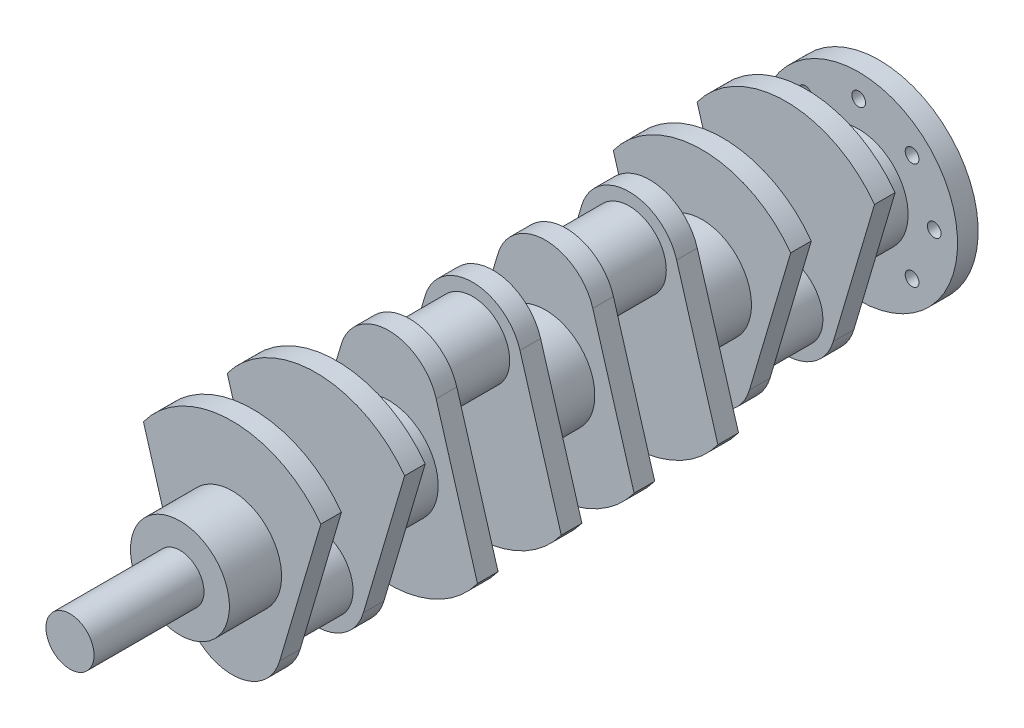
SolidWorks part; units mm, degrees
ref_plane "Front Plane" through (0, 0, 0) normal (0, 0, 1) x (1, 0, 0)
ref_plane "Top Plane" through (0, 0, 0) normal (0, 1, 0) x (1, 0, 0)
ref_plane "Right Plane" through (0, 0, 0) normal (1, 0, 0) x (0, 0, -1)
sketch "Sketch1" plane through (0, 0, 0) normal (0, 0, 1) x (1, 0, 0)
  line L0 (0, 0) -> (0, 85088.2175) construction
  line L1 (0, 0) -> (-85088.2175, 0) construction
  line L2 (-64.5699, 47.2306) -> (-34.5175, -54.2246)
  line L3 (64.5699, 47.2306) -> (34.5175, -54.2246)
  circle A0 centre (0, -44) radius 36
  arc A1 (-64.5699, 47.2306) -> (64.5699, 47.2306) centre (0, 0) cw
  dimension "D1" = 72
  dimension "D3" = 80
  dimension "D2" = 44
  dimension "D4" = 33
extrude "Boss-Extrude1" add sketch "Sketch1" along normal blind 15 contours A1 L2 A0 L3 | A0
sketch "Sketch2" plane through (0, 0, 15) normal (0, 0, 1) x (1, 0, 0)
  circle A0 centre (0, -44) radius 27
  dimension "D1" = 54
extrude "Boss-Extrude2" add sketch "Sketch2" along normal blind 46
sketch "Sketch3" plane through (0, 0, 0) normal (0, 0, -1) x (-1, 0, 0)
  circle A0 centre (0, 0) radius 36
  dimension "D1" = 72
extrude "Boss-Extrude3" add sketch "Sketch3" along normal blind 38
ref_plane "Plane1" through (0, 0, 38) normal (0, 0, 1) x (1, 0, 0)
mirror "Mirror1" about plane through (0, 0, 38) normal (0, 0, 1) of "Boss-Extrude3", "Boss-Extrude1"
ref_plane "Plane4" through (0, 0, -19) normal (0, 0, -1) x (-1, 0, 0)
mirror "Mirror6" about plane through (0, 0, -19) normal (0, 0, -1) of bodies 104
move or copy body "Body-Move/Copy1" bodies to move or copy 111 copy no rotation origin (0, 0, -76) rotation axis (1, 0, 0) rotation angle 180
ref_plane "Plane5" through (0, 0, -133) normal (0, 0, -1) x (-1, 0, 0)
mirror "Mirror7" about plane through (0, 0, -133) normal (0, 0, -1) of bodies 112 104
sketch "Sketch4" plane through (0, 0, 114) normal (0, 0, 1) x (1, 0, 0)
  circle A0 centre (0, 0) radius 17.5
  dimension "D1" = 35
extrude "Boss-Extrude4" add sketch "Sketch4" along normal blind 80
sketch "Sketch5" plane through (0, 0, -380) normal (0, 0, -1) x (-1, 0, 0)
  circle A0 centre (0, 0) radius 72
  circle A1 centre (0, 0) radius 55 construction
  circle A2 centre (0, 55) radius 5
  circle A3 centre (38.8909, 38.8909) radius 5
  circle A4 centre (55, 0) radius 5
  circle A5 centre (38.8909, -38.8909) radius 5
  circle A6 centre (0, -55) radius 5
  circle A7 centre (-38.8909, -38.8909) radius 5
  circle A8 centre (-55, 0) radius 5
  circle A9 centre (-38.8909, 38.8909) radius 5
  point P23 (0, 0)
  dimension "D1" = 144
  dimension "D2" = 10
  dimension "D4" = 110
  dimension "D3" = 8
extrude "Boss-Extrude5" add sketch "Sketch5" along normal blind 15
combine bodies "Combine1" operation type add bodies to combine 115 112 113 116
